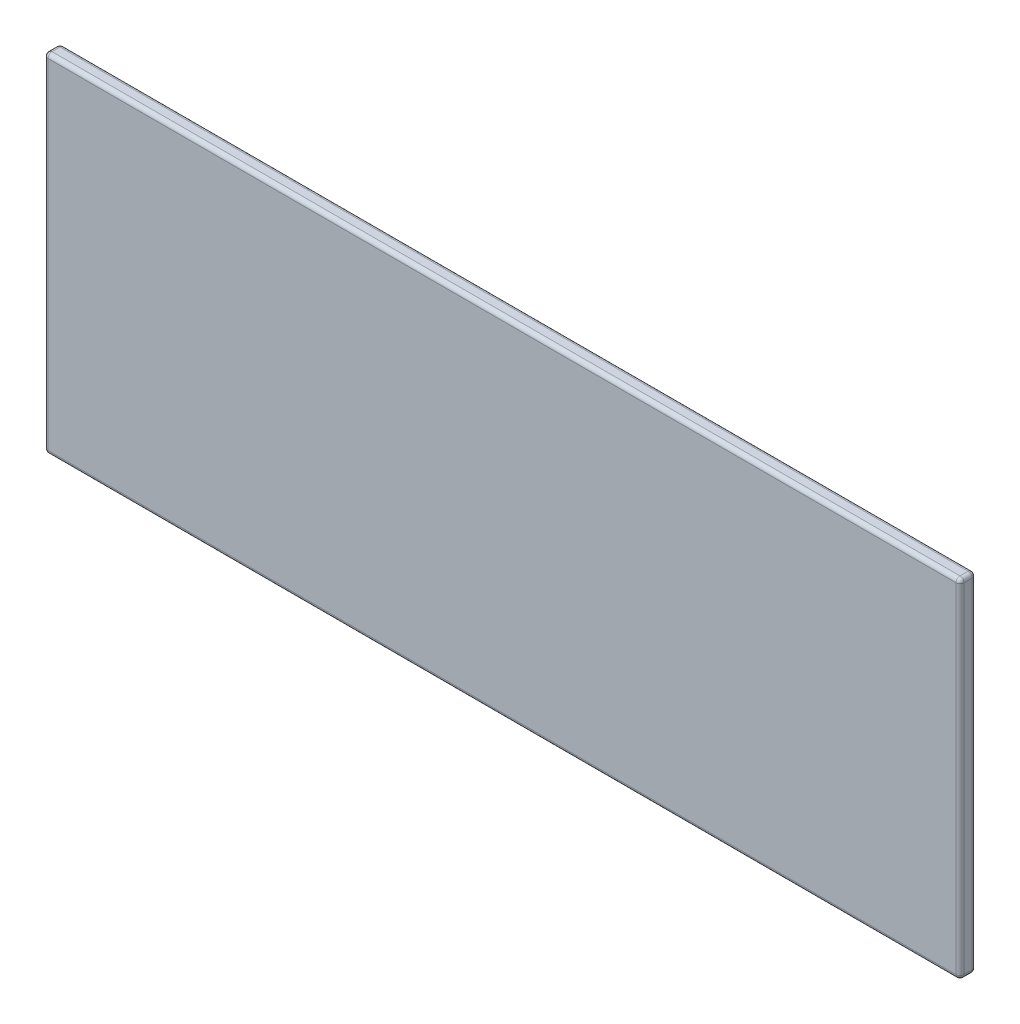
SolidWorks part; units mm, degrees
ref_plane "Front Plane" through (0, 0, 0) normal (0, 0, 1) x (1, 0, 0)
ref_plane "Top Plane" through (0, 0, 0) normal (0, 1, 0) x (1, 0, 0)
ref_plane "Right Plane" through (0, 0, 0) normal (1, 0, 0) x (0, 0, -1)
sketch "Sketch1" plane through (0, 0, 0) normal (0, 0, 1) x (1, 0, 0)
  line L1 (-57.35, -21.75) -> (57.35, -21.75)
  line L2 (-57.35, -21.75) -> (-57.35, 21.75)
  line L3 (-57.35, 21.75) -> (57.35, 21.75)
  line L4 (57.35, -21.75) -> (57.35, 21.75)
  line L5 (-57.35, -21.75) -> (57.35, 21.75) construction
  line L6 (-57.35, 21.75) -> (57.35, -21.75) construction
  point P0 (0, 0)
  dimension "D1" = 114.7
  dimension "D2" = 43.5
extrude "Boss-Extrude1" add sketch "Sketch1" along normal blind 2
fillet "Fillet1" radius 0.5 12 edges at (0, -21.75, 2) (0, -21.75, 0) (-57.35, 0, 2) (-57.35, -21.75, 1) (-57.35, 0, 0) (0, 21.75, 2) (-57.35, 21.75, 1) (0, 21.75, 0) (57.35, -21.75, 1) (57.35, 0, 2) (57.35, 21.75, 1) (57.35, 0, 0)
